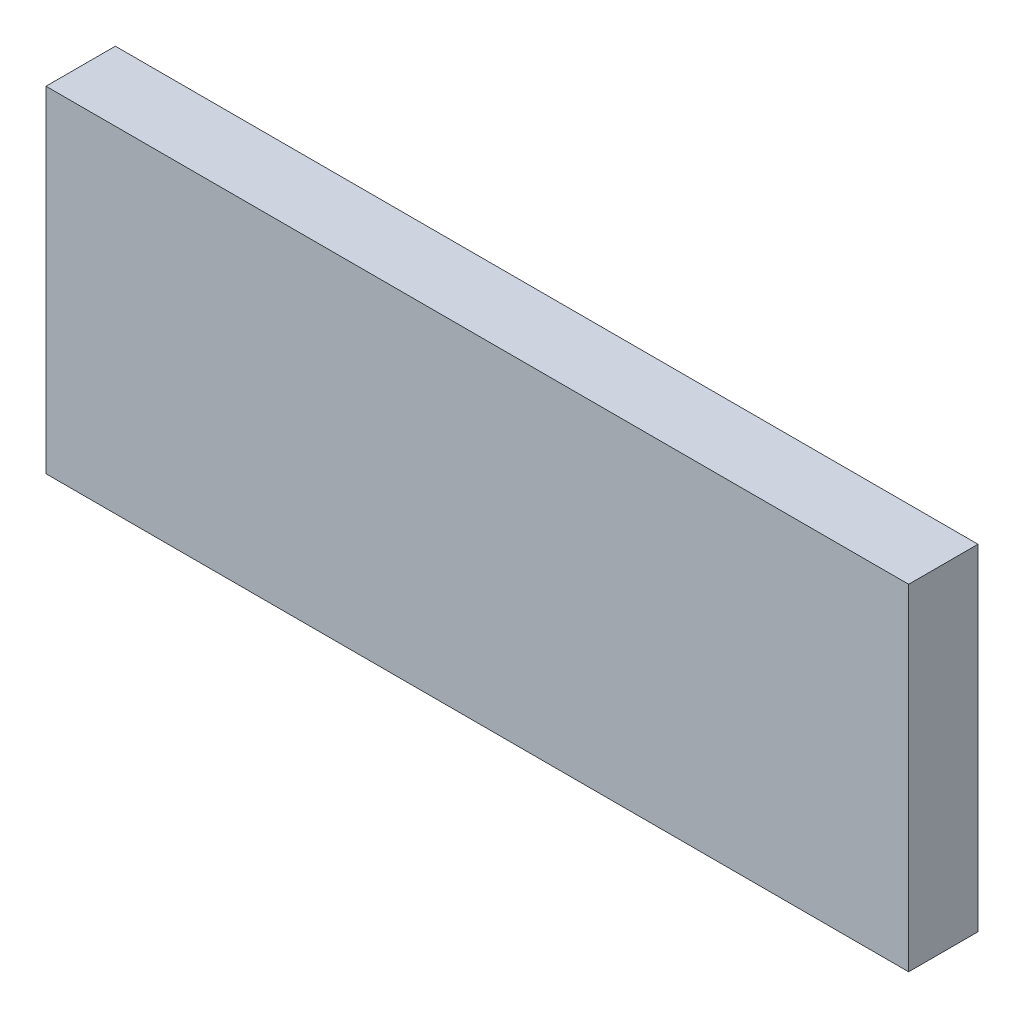
SolidWorks part; units mm, degrees
ref_plane "Front Plane" through (0, 0, 0) normal (0, 0, 1) x (1, 0, 0)
ref_plane "Top Plane" through (0, 0, 0) normal (0, 1, 0) x (1, 0, 0)
ref_plane "Right Plane" through (0, 0, 0) normal (1, 0, 0) x (0, 0, -1)
sketch "Sketch1" plane through (0, 0, 0) normal (0, 0, 1) x (1, 0, 0)
  line L1 (0, 0) -> (78.994, 0)
  line L2 (0, 0) -> (0, 30.734)
  line L3 (0, 30.734) -> (78.994, 30.734)
  line L4 (78.994, 0) -> (78.994, 30.734)
  dimension "D1" = 30.734
  dimension "D2" = 78.994
extrude "Boss-Extrude1" add sketch "Sketch1" along normal blind 6.35
